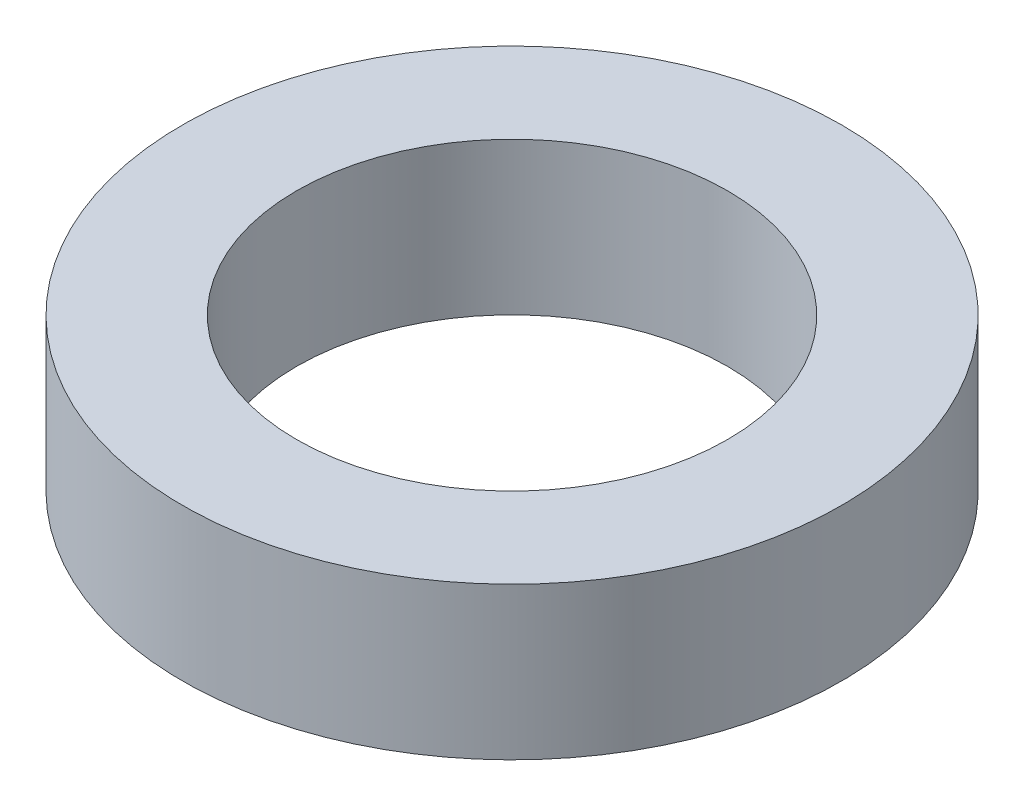
SolidWorks part; units mm, degrees
ref_plane "Front Plane" through (0, 0, 0) normal (0, 0, 1) x (1, 0, 0)
ref_plane "Top Plane" through (0, 0, 0) normal (0, 1, 0) x (1, 0, 0)
ref_plane "Right Plane" through (0, 0, 0) normal (1, 0, 0) x (0, 0, -1)
sketch "Sketch1" plane through (0, 0, 0) normal (0, 1, 0) x (1, 0, 0)
  circle A0 centre (0, 0) radius 16.51
  circle A1 centre (0, 0) radius 10.795
  dimension "D1" = 33.02
  dimension "D2" = 21.59
extrude "Boss-Extrude1" add sketch "Sketch1" along normal blind 7.62
